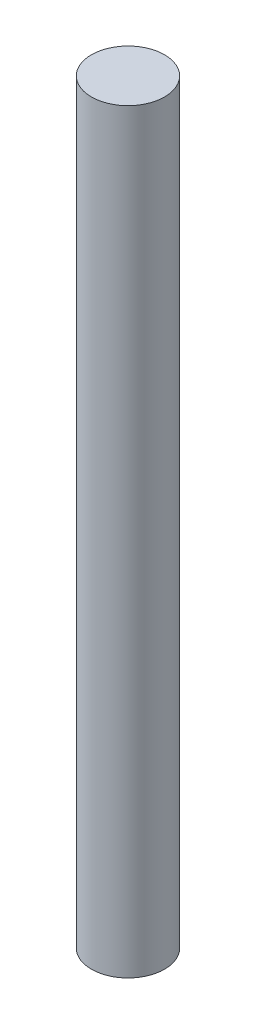
SolidWorks part; units mm, degrees
ref_plane "Front Plane" through (0, 0, 0) normal (0, 0, 1) x (1, 0, 0)
ref_plane "Top Plane" through (0, 0, 0) normal (0, 1, 0) x (1, 0, 0)
ref_plane "Right Plane" through (0, 0, 0) normal (1, 0, 0) x (0, 0, -1)
sketch "Sketch1" plane through (0, 0, 0) normal (0, 1, 0) x (1, 0, 0)
  circle A0 centre (0, 0) radius 3
  dimension "D1" = 6
extrude "Boss-Extrude1" add sketch "Sketch1" along normal blind 62
